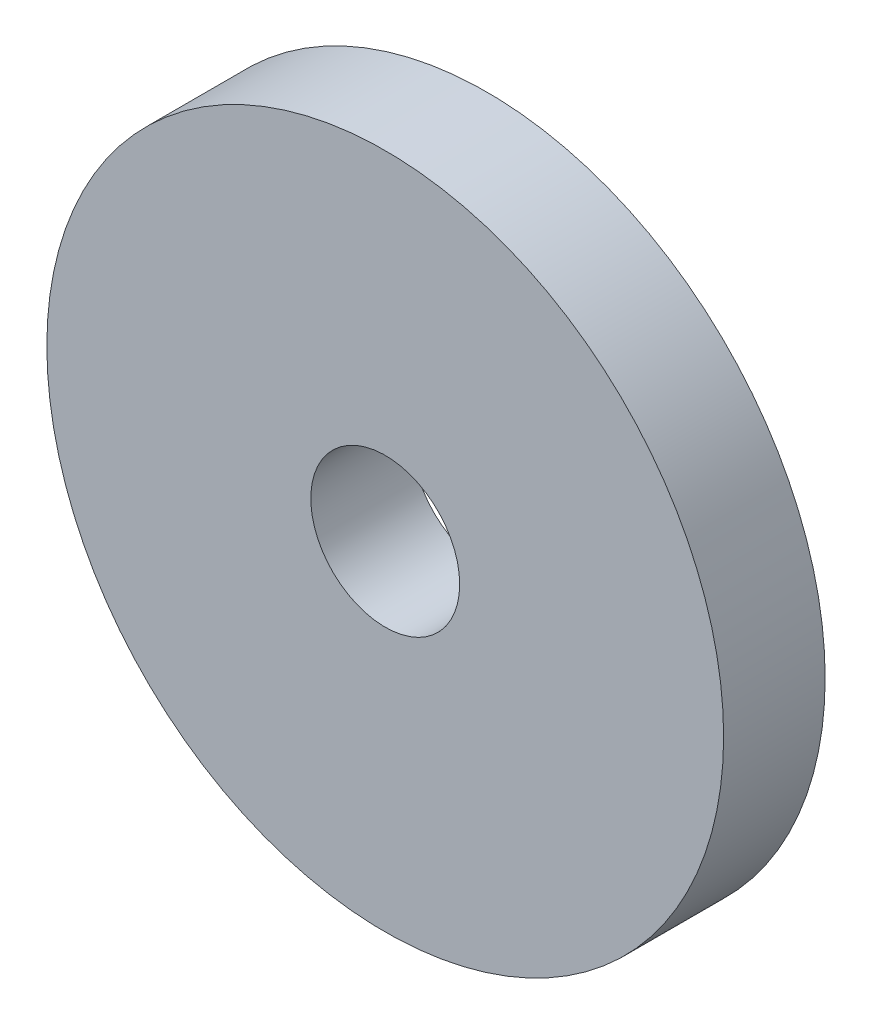
SolidWorks part; units mm, degrees
ref_plane "前视基准面" through (0, 0, 0) normal (0, 0, 1) x (1, 0, 0)
ref_plane "上视基准面" through (0, 0, 0) normal (0, 1, 0) x (1, 0, 0)
ref_plane "右视基准面" through (0, 0, 0) normal (1, 0, 0) x (0, 0, -1)
sketch "草图1" plane through (0, 0, 0) normal (0, 0, 1) x (1, 0, 0)
  circle A0 centre (0, 0) radius 5
  circle A1 centre (0, 0) radius 1.1
  dimension "D1" = 10
  dimension "D2" = 2.2
extrude "凸台-拉伸1" add sketch "草图1" along normal blind 1.5
